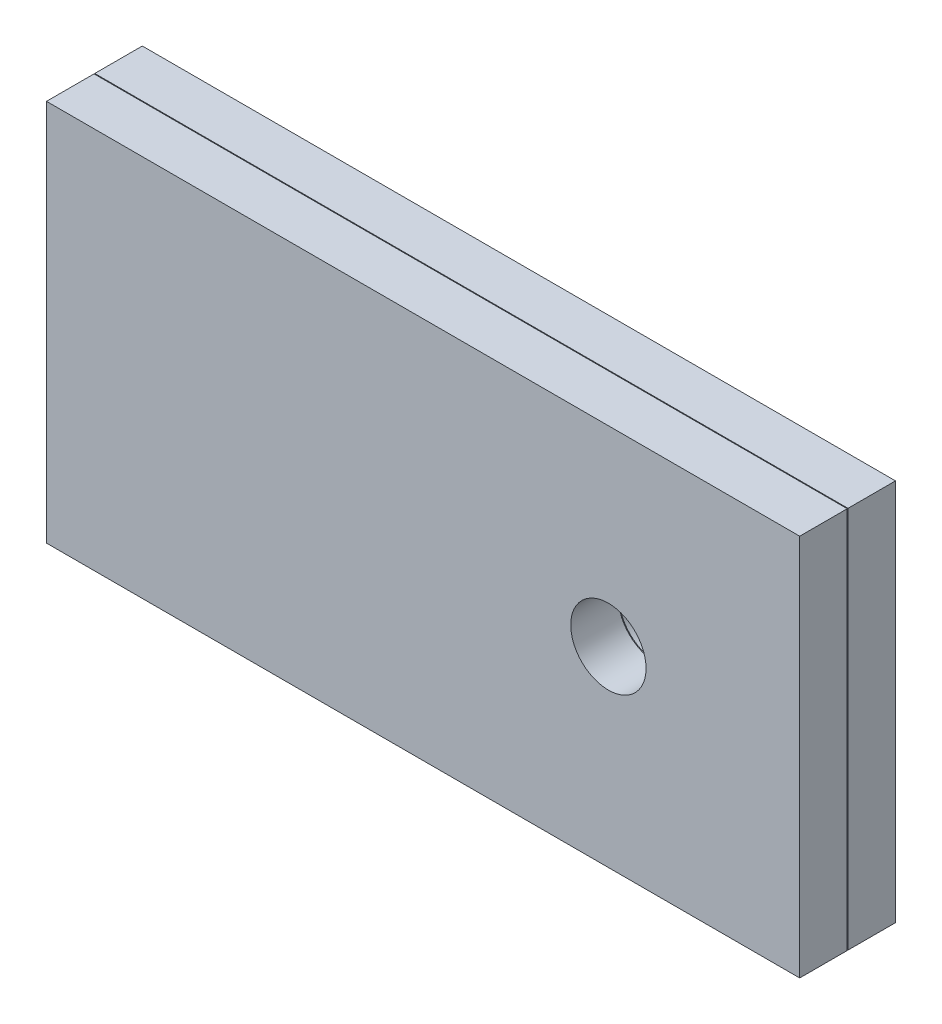
SolidWorks part; units mm, degrees
ref_plane "Alzado" through (0, 0, 0) normal (0, 0, 1) x (1, 0, 0)
ref_plane "Planta" through (0, 0, 0) normal (0, 1, 0) x (1, 0, 0)
ref_plane "Vista lateral" through (0, 0, 0) normal (1, 0, 0) x (0, 0, -1)
sketch "Croquis1" plane through (0, 0, 0) normal (0, 0, 1) x (1, 0, 0)
  line L1 (-50, 25.4) -> (50, 25.4)
  line L2 (-50, 25.4) -> (-50, -25.4)
  line L3 (-50, -25.4) -> (50, -25.4)
  line L4 (50, 25.4) -> (50, -25.4)
  line L5 (-50, 25.4) -> (50, -25.4) construction
  line L6 (-50, -25.4) -> (50, 25.4) construction
  point P0 (0, 0)
  dimension "D1" = 100
  dimension "D2" = 50.8
extrude "Saliente-Extruir1" add sketch "Croquis1" along normal blind 6.31
sketch "Croquis2" plane through (50, 0, 0) normal (1, 0, 0) x (0, 0, -1)
  line L0 (0.1, -25.4) -> (6.41, -25.4)
  line L1 (6.41, -25.4) -> (6.41, 25.4)
  line L2 (6.41, 25.4) -> (0.1, 25.4)
  line L3 (0, -25.4) -> (0, 25.4) construction
  line L4 (0.1, -25.4) -> (0.1, 25.4)
  dimension "D1" = 0.1
  dimension "D2" = 6.31
extrude "Saliente-Extruir2" add sketch "Croquis2" against normal blind 100 separate body
sketch "Croquis3" plane through (0, 0, -6.41) normal (0, 0, -1) x (-1, 0, 0)
  line L0 (50, 0) -> (0.8, 0) construction
  line L1 (50, -25.4) -> (50, 25.4) construction
  line L2 (0.8, 0) -> (0.8, 25.4) construction
  line L3 (50, 25.4) -> (-50, 25.4) construction
  line L4 (-50, -25.4) -> (-50, 25.4) construction
  line L5 (0.8, 0) -> (-50, 0) construction
  line L6 (-50, 0) -> (-24.6, 0) construction
  line L7 (-24.6, 0) -> (-24.6, 25.4) construction
  line L8 (-24.6, 25.4) -> (-32.4319, 29.7338) construction
  circle A0 centre (-24.6, 0) radius 5
  dimension "D2" = 10
  dimension "D1" = 50.8
extrude "Cortar-Extruir1" cut sketch "Croquis3" against normal blind 50
